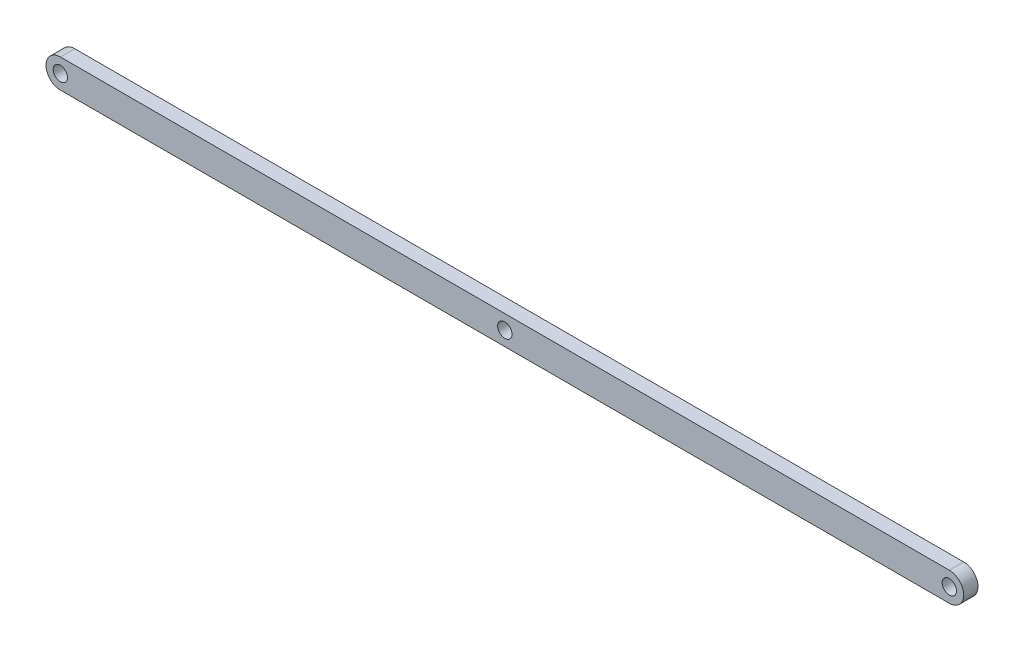
SolidWorks part; units mm, degrees
ref_plane "Front Plane" through (0, 0, 0) normal (0, 0, 1) x (1, 0, 0)
ref_plane "Top Plane" through (0, 0, 0) normal (0, 1, 0) x (1, 0, 0)
ref_plane "Right Plane" through (0, 0, 0) normal (1, 0, 0) x (0, 0, -1)
sketch "Sketch1" plane through (0, 0, 0) normal (0, 0, 1) x (1, 0, 0)
  line L0 (310, 0) -> (-310, 0) construction
  line L3 (310, -10) -> (-310, -10)
  line L4 (310, 10) -> (-310, 10)
  arc A5 (310, -10) -> (310, 10) centre (310, 0) ccw
  arc A6 (-310, 10) -> (-310, -10) centre (-310, 0) ccw
  circle A10 centre (-310, 0) radius 5
  circle A11 centre (310, 0) radius 5
  circle A12 centre (0, 0) radius 5
  point P3 (0, 0)
  point P4 (0, 0)
extrude "Boss-Extrude1" add sketch "Sketch1" along normal blind 10
